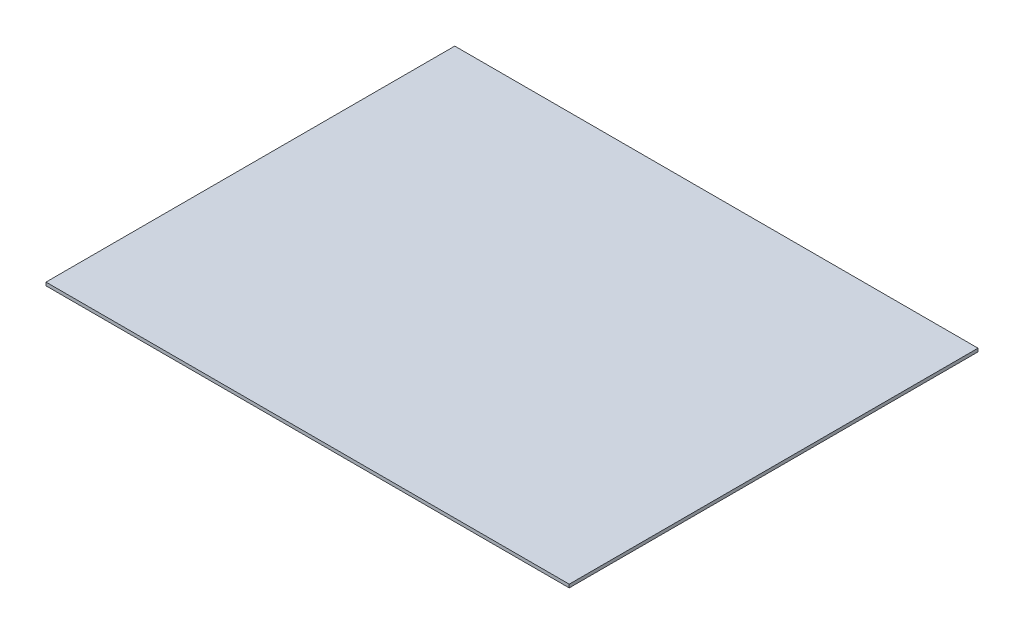
SolidWorks part; units mm, degrees
ref_plane "Front Plane" through (0, 0, 0) normal (0, 0, 1) x (1, 0, 0)
ref_plane "Top Plane" through (0, 0, 0) normal (0, 1, 0) x (1, 0, 0)
ref_plane "Right Plane" through (0, 0, 0) normal (1, 0, 0) x (0, 0, -1)
sketch "Sketch1" plane through (0, 0, 0) normal (0, 1, 0) x (1, 0, 0)
  line L1 (-80, 62.5) -> (80, 62.5)
  line L2 (-80, 62.5) -> (-80, -62.5)
  line L3 (-80, -62.5) -> (80, -62.5)
  line L4 (80, 62.5) -> (80, -62.5)
  point P4 (0, 62.5)
  point P6 (80, 0)
  dimension "D1" = 160
  dimension "D2" = 125
extrude "Boss-Extrude1" add sketch "Sketch1" along normal blind 1
